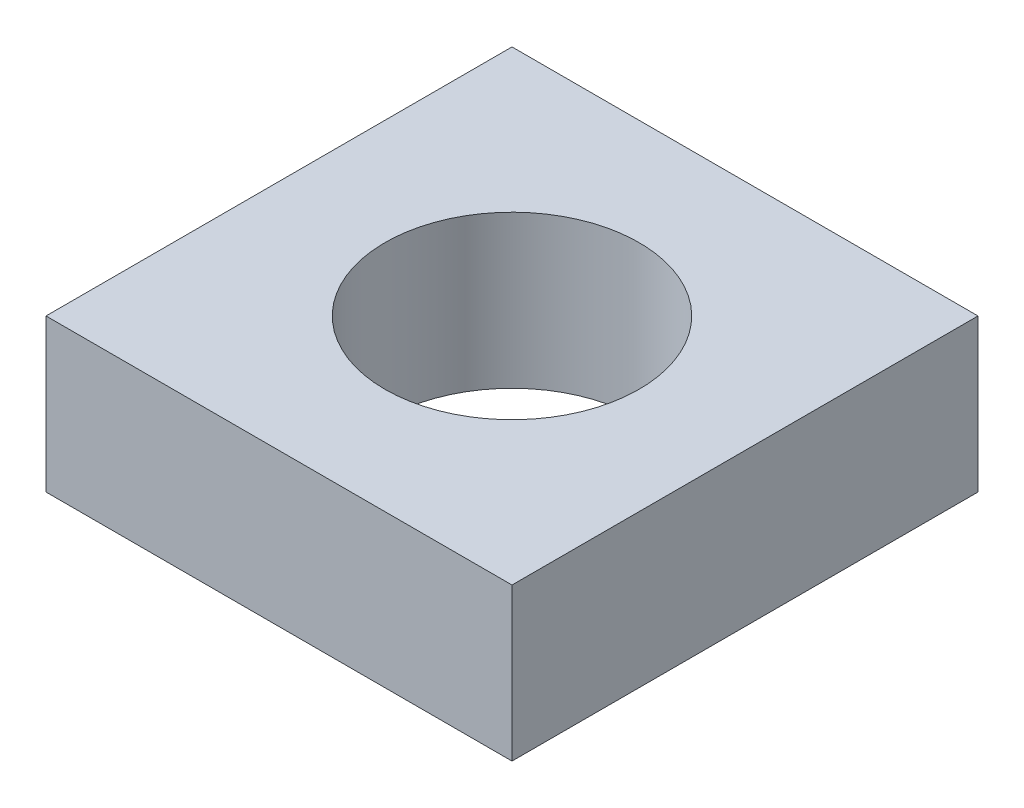
SolidWorks part; units mm, degrees
ref_plane "Płaszczyzna przednia" through (0, 0, 0) normal (0, 0, 1) x (1, 0, 0)
ref_plane "Płaszczyzna górna" through (0, 0, 0) normal (0, 1, 0) x (1, 0, 0)
ref_plane "Płaszczyzna prawa" through (0, 0, 0) normal (1, 0, 0) x (0, 0, -1)
sketch "Szkic1" plane through (0, 0, 0) normal (0, 1, 0) x (1, 0, 0)
  line L0 (0, 2.75) -> (5.5, 2.75) construction
  line L1 (0, 0) -> (5.5, 0)
  line L2 (0, 0) -> (0, 5.5)
  line L3 (0, 5.5) -> (5.5, 5.5)
  line L4 (5.5, 0) -> (5.5, 5.5)
  circle A0 centre (2.75, 2.75) radius 1.5
extrude "Dodanie-wyciągnięcie1" add sketch "Szkic1" along normal blind 1.8
